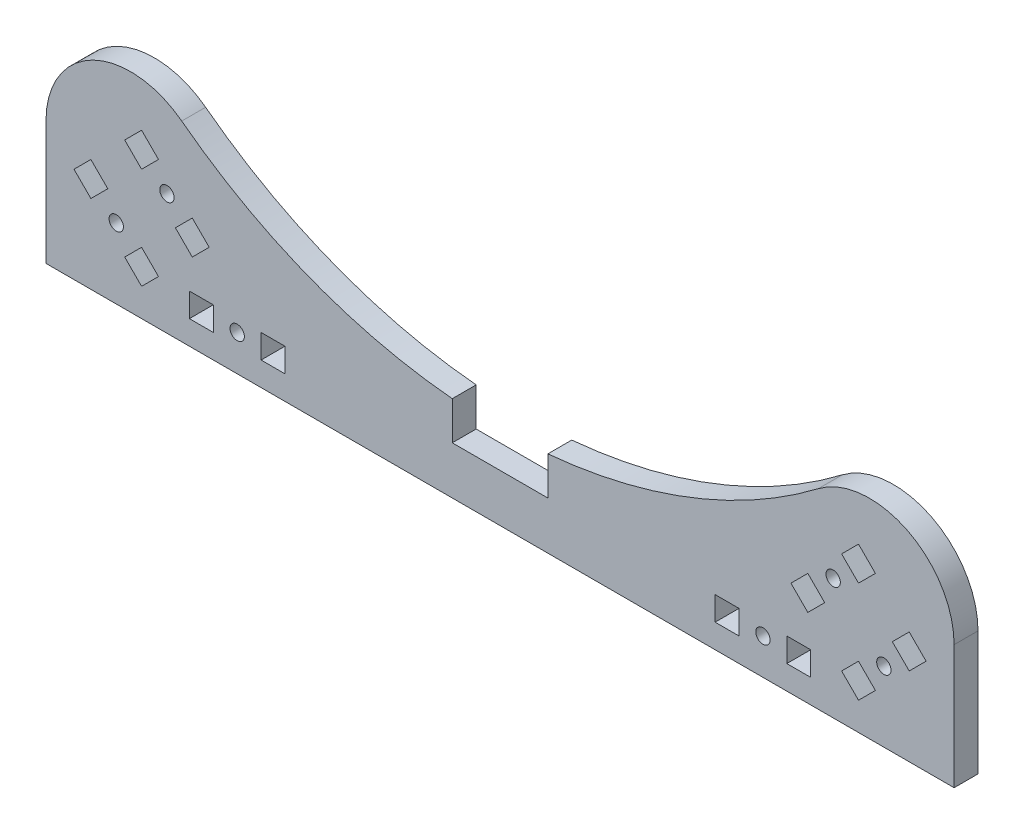
SolidWorks part; units mm, degrees
ref_plane "Plan de face" through (0, 0, 0) normal (0, 0, 1) x (1, 0, 0)
ref_plane "Plan de dessus" through (0, 0, 0) normal (0, 1, 0) x (1, 0, 0)
ref_plane "Plan de droite" through (0, 0, 0) normal (1, 0, 0) x (0, 0, -1)
sketch "Sketch1" plane through (0, 0, 0) normal (0, 0, 1) x (1, 0, 0)
  line L0 (-95, 0) -> (95, 0)
  line L1 (95, 0) -> (95, 25.9232)
  line L2 (-95, 0) -> (-95, 25.9232)
  line L3 (0, 0) -> (0, 70.426) construction
  line L4 (75, 20) -> (-75, 20) construction
  line L5 (86.727, 8.273) -> (63.0524, 31.9476) construction
  line L6 (75, 20) -> (92.9429, 37.9429) construction
  line L7 (-10, 18) -> (-10, 10)
  line L8 (-10, 10) -> (10, 10)
  line L9 (10, 10) -> (10, 18)
  arc A0 (95, 25.9232) -> (66.603, 40) centre (77.3125, 25.9232) ccw
  arc A1 (-95, 25.9232) -> (-66.603, 40) centre (-77.3125, 25.9232) cw
  arc A2 (-66.603, 40) -> (66.603, 40) centre (0, 127.5445) ccw construction
  arc A3 (10, 18) -> (66.603, 40) centre (0, 127.5445) ccw
  arc A4 (-10, 18) -> (-66.603, 40) centre (0, 127.5445) cw
  point P23 (-58.8796, 40)
  point P24 (60.7537, 37.9429)
  line B0 (76.7678, 11.1612) -> (83.8388, 18.2322) construction
  line B1 (75, 12.9289) -> (71.4645, 9.3934)
  line B2 (75, 12.9289) -> (78.5355, 9.3934)
  line B3 (78.5355, 9.3934) -> (75, 5.8579)
  line B4 (71.4645, 9.3934) -> (75, 5.8579)
  line B5 (82.0711, 20) -> (85.6066, 23.5355)
  line B6 (82.0711, 20) -> (85.6066, 16.4645)
  line B7 (85.6066, 16.4645) -> (89.1421, 20)
  line B8 (85.6066, 23.5355) -> (89.1421, 20)
  circle B9 centre (80.3033, 14.6967) radius 1.5
  line B10 (66.1612, 21.7678) -> (73.2322, 28.8388) construction
  line B11 (64.3934, 23.5355) -> (60.8579, 20)
  line B12 (64.3934, 23.5355) -> (67.9289, 20)
  line B13 (67.9289, 20) -> (64.3934, 16.4645)
  line B14 (60.8579, 20) -> (64.3934, 16.4645)
  line B15 (71.4645, 30.6066) -> (75, 34.1421)
  line B16 (71.4645, 30.6066) -> (75, 27.0711)
  line B17 (75, 27.0711) -> (78.5355, 30.6066)
  line B18 (75, 34.1421) -> (78.5355, 30.6066)
  circle B19 centre (69.6967, 25.3033) radius 1.5
  line B20 (-64.3934, 23.5355) -> (-60.8579, 20)
  line B21 (-64.3934, 23.5355) -> (-67.9289, 20)
  line B22 (-67.9289, 20) -> (-64.3934, 16.4645)
  line B23 (-60.8579, 20) -> (-64.3934, 16.4645)
  line B24 (-71.4645, 30.6066) -> (-75, 34.1421)
  line B25 (-71.4645, 30.6066) -> (-75, 27.0711)
  line B26 (-75, 27.0711) -> (-78.5355, 30.6066)
  line B27 (-75, 34.1421) -> (-78.5355, 30.6066)
  circle B28 centre (-69.6967, 25.3033) radius 1.5
  line B29 (-75, 12.9289) -> (-71.4645, 9.3934)
  line B30 (-75, 12.9289) -> (-78.5355, 9.3934)
  line B31 (-78.5355, 9.3934) -> (-75, 5.8579)
  line B32 (-71.4645, 9.3934) -> (-75, 5.8579)
  line B33 (-82.0711, 20) -> (-85.6066, 23.5355)
  line B34 (-82.0711, 20) -> (-85.6066, 16.4645)
  line B35 (-85.6066, 16.4645) -> (-89.1421, 20)
  line B36 (-85.6066, 23.5355) -> (-89.1421, 20)
  circle B37 centre (-80.3033, 14.6967) radius 1.5
  line B38 (50, 10) -> (45, 10)
  line B39 (50, 10) -> (50, 5)
  line B40 (50, 5) -> (45, 5)
  line B41 (45, 10) -> (45, 5)
  line B42 (60, 10) -> (65, 10)
  line B43 (60, 10) -> (60, 5)
  line B44 (60, 5) -> (65, 5)
  line B45 (65, 10) -> (65, 5)
  line B46 (55, 7.5) -> (55, 14.4724) construction
  circle B47 centre (55, 7.5) radius 1.5
  line B48 (-50, 10) -> (-45, 10)
  line B49 (-50, 10) -> (-50, 5)
  line B50 (-50, 5) -> (-45, 5)
  line B51 (-45, 10) -> (-45, 5)
  line B52 (-60, 10) -> (-65, 10)
  line B53 (-60, 10) -> (-60, 5)
  line B54 (-60, 5) -> (-65, 5)
  line B55 (-65, 10) -> (-65, 5)
  circle B56 centre (-55, 7.5) radius 1.5
  dimension "D1" = 110
  dimension "D9" = 40
  dimension "D2" = 190
  dimension "D3" = 20
  dimension "D4" = 150
  dimension "D5" = 15
  dimension "D6" = 45
  dimension "D7" = 10
  dimension "D8" = 20
  dimension "D10" = 18
  dimension "D11" = 5
  dimension "D12" = 55
sketch_block_instance "Trou M3 plots 5mm-1"
sketch_block "Trou M3 plots 5mm" parameters "D2"=3, "D1"=5, "D3"=5, "D4"=10
sketch_block_instance "Trou M3 plots 5mm-2"
sketch_block_instance "Trou M3 plots 5mm-4"
sketch_block_instance "Trou M3 plots 5mm-5"
sketch_block_instance "Trou M3 plots 5mm-6"
sketch_block_instance "Trou M3 plots 5mm-7"
extrude "Boss-Extrude1" add sketch "Sketch1" along normal blind 5
